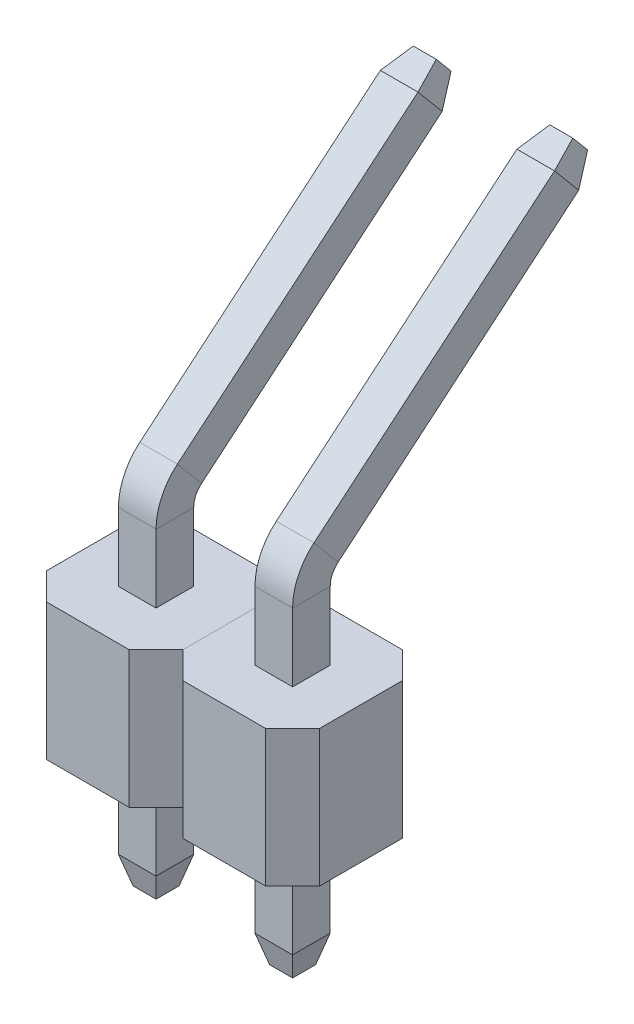
SolidWorks part; units mm, degrees
ref_plane "Front Plane" through (0, 0, 0) normal (0, 0, 1) x (1, 0, 0)
ref_plane "Top Plane" through (0, 0, 0) normal (0, 1, 0) x (1, 0, 0)
ref_plane "Right Plane" through (0, 0, 0) normal (1, 0, 0) x (0, 0, -1)
sketch "Sketch3" plane through (0, 0, 0) normal (0, 1, 0) x (1, 0, 0)
  line L1 (-1.27, 1.27) -> (1.27, 1.27)
  line L2 (-1.27, 1.27) -> (-1.27, -1.27)
  line L3 (-1.27, -1.27) -> (1.27, -1.27)
  line L4 (1.27, 1.27) -> (1.27, -1.27)
  line L5 (-1.27, 1.27) -> (1.27, -1.27) construction
  line L6 (-1.27, -1.27) -> (1.27, 1.27) construction
  line L7 (0.3175, -0.3175) -> (-0.3175, -0.3175)
  line L8 (0.3175, -0.3175) -> (0.3175, 0.3175)
  line L9 (0.3175, 0.3175) -> (-0.3175, 0.3175)
  line L10 (-0.3175, -0.3175) -> (-0.3175, 0.3175)
  line L11 (0.3175, -0.3175) -> (-0.3175, 0.3175) construction
  line L12 (0.3175, 0.3175) -> (-0.3175, -0.3175) construction
  point P0 (0, 0)
  point P7 (0, 0)
  dimension "D1" = 2.54
  dimension "D2" = 0.635
extrude "Boss-Extrude1" add sketch "Sketch3" along normal mid plane 2.54
chamfer "Chamfer1" distance 0.5 angle 45 4 edges at (-1.27, 0, 1.27) (-1.27, 0, -1.27) (1.27, 0, -1.27) (1.27, 0, 1.27)
sketch "Sketch5" plane through (0, 1.27, 0) normal (0, 1, 0) x (1, 0, 0)
  line L1 (0.35, -0.35) -> (-0.35, -0.35)
  line L2 (0.35, -0.35) -> (0.35, 0.35)
  line L3 (0.35, 0.35) -> (-0.35, 0.35)
  line L4 (-0.35, -0.35) -> (-0.35, 0.35)
  line L5 (0.35, -0.35) -> (-0.35, 0.35) construction
  line L6 (0.35, 0.35) -> (-0.35, -0.35) construction
  point P0 (0, 0)
  dimension "D1" = 0.7
sketch "Sketch9" plane through (0, 0, 0) normal (1, 0, 0) x (0, 0, -1)
  line L0 (0, -3.048) -> (0, 2.54)
  line L1 (0.2722, 3.1237) -> (4.7474, 6.8789)
  line L2 (-0.35, 1.27) -> (0.35, 1.27) construction
  line L4 (-0.77, 1.27) -> (0.77, 1.27) construction
  arc A0 (0, 2.54) -> (0.2722, 3.1237) centre (0.762, 2.54) cw
  dimension "D2" = 0.762
  dimension "D1" = 1.27
  dimension "D3" = 50
  dimension "D4" = 5.842
  dimension "D5" = 4.318
sweep "Sweep1" add profiles "Sketch5" path "Sketch9"
sketch "Sketch10" plane through (0, 5.1798, -6.1731) normal (0, 0.6428, -0.766) x (1, 0, 0)
  line L4 (-0.35, -1.8679) -> (-0.35, -2.5679)
  line L5 (-0.35, -2.5679) -> (0.35, -2.5679)
  line L6 (0.35, -2.5679) -> (0.35, -1.8679)
  line L7 (0.35, -1.8679) -> (-0.35, -1.8679)
  line L8 (-0.35, -1.8679) -> (-0.35, -2.5679)
  line L9 (-0.35, -2.5679) -> (0.35, -2.5679)
  line L10 (0.35, -2.5679) -> (0.35, -1.8679)
  line L11 (0.35, -1.8679) -> (-0.35, -1.8679)
  dimension "D1" = 0
extrude "Boss-Extrude5" add sketch "Sketch10" along normal blind 0.508 draft 15
sketch "Sketch11" plane through (0, -3.048, 0) normal (0, -1, 0) x (1, 0, 0)
  line L4 (-0.35, 0.35) -> (-0.35, -0.35)
  line L5 (-0.35, -0.35) -> (0.35, -0.35)
  line L6 (0.35, -0.35) -> (0.35, 0.35)
  line L7 (0.35, 0.35) -> (-0.35, 0.35)
  line L8 (-0.35, 0.35) -> (-0.35, -0.35)
  line L9 (-0.35, -0.35) -> (0.35, -0.35)
  line L10 (0.35, -0.35) -> (0.35, 0.35)
  line L11 (0.35, 0.35) -> (-0.35, 0.35)
  dimension "D1" = 0
extrude "Boss-Extrude6" add sketch "Sketch11" along normal blind 0.508 draft 15
pattern_linear "LPattern1" count 2 spacing 2.54 along (1, 0, 0) of "Boss-Extrude1"
